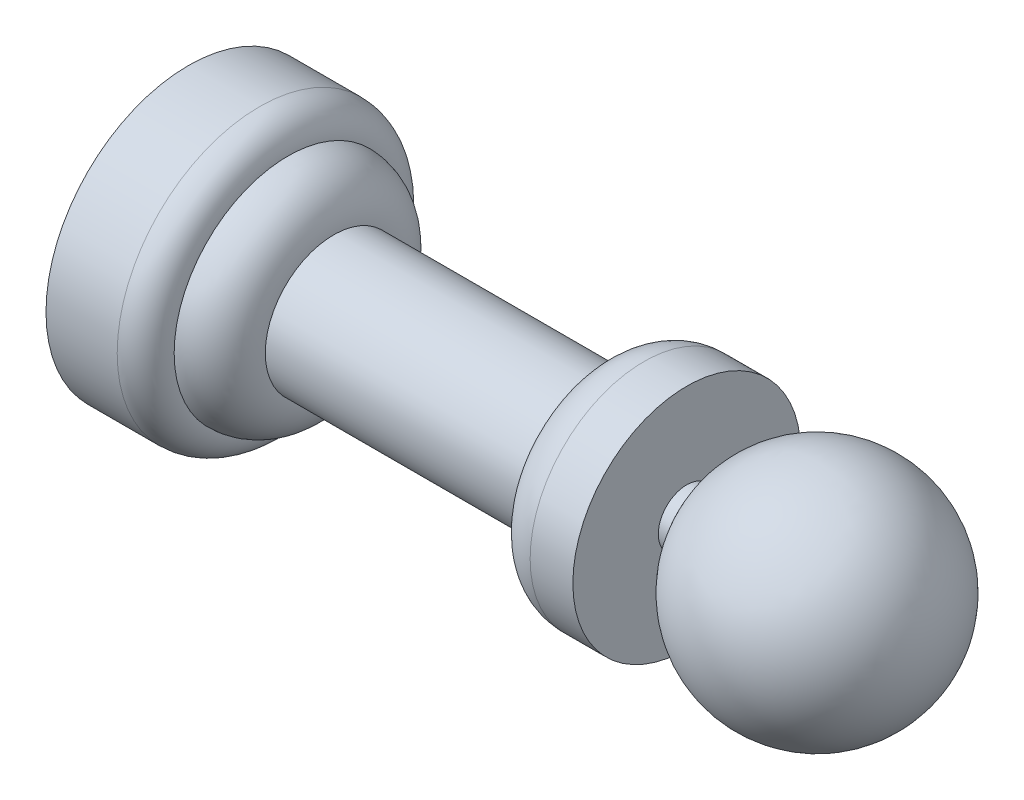
SolidWorks part; units mm, degrees
ref_plane "Спереди" through (0, 0, 0) normal (0, 0, 1) x (1, 0, 0)
ref_plane "Сверху" through (0, 0, 0) normal (0, 1, 0) x (1, 0, 0)
ref_plane "Справа" through (0, 0, 0) normal (1, 0, 0) x (0, 0, -1)
sketch "Эскиз1" plane through (0, 0, 0) normal (0, 0, 1) x (1, 0, 0)
  line L0 (0, 0) -> (52.2088, 0) construction
  line L1 (55, 0) -> (-55, 0) construction
  line L2 (0, 0) -> (0, 10)
  line L3 (0, 10) -> (5, 10)
  line L4 (7, 8) -> (7, 0)
  line L5 (5, 10) -> (5, 0) construction
  line L6 (7, 8) -> (0, 8) construction
  line L7 (10.2, 0) -> (10.2, 4.8)
  line L8 (10.2, 4.8) -> (28.8, 4.8)
  line L9 (32, 0) -> (32, 8)
  line L10 (32, 8) -> (35, 8)
  line L11 (35, 8) -> (35, 0)
  line L12 (28.8, 4.8) -> (32, 4.8) construction
  line L13 (35, 2) -> (36.4, 2)
  line L14 (36.4, 2) -> (36.4, 0)
  line L15 (1, 0) -> (1, 5.25)
  line L16 (1, 5.25) -> (3.5, 5.25)
  line L17 (3.5, 5.25) -> (3.5, 0)
  line L18 (0, 0) -> (52.146, 0)
  arc A0 (5, 10) -> (7, 8) centre (5, 8) cw
  arc A1 (7, 8) -> (10.2, 4.8) centre (7, 4.8) cw
  arc A2 (28.8, 4.8) -> (32, 8) centre (32, 4.8) cw
  arc A3 (36.4, 2) -> (52.146, 0) centre (44.146, 0) cw
  dimension "D3" = 2
  dimension "D5" = 10.2
  dimension "D6" = 3.2
  dimension "D7" = 18.6
  dimension "D10" = 3.2
  dimension "D13" = 8
  dimension "D1" = 10
  dimension "D2" = 5
  dimension "D4" = 4.8
  dimension "D8" = 8
  dimension "D9" = 3
  dimension "D11" = 2
  dimension "D12" = 1.4
  dimension "D14" = 1
  dimension "D15" = 2.5
  dimension "D16" = 5.25
revolve "Повернуть8" add sketch "Эскиз1" angle 360 about L0
